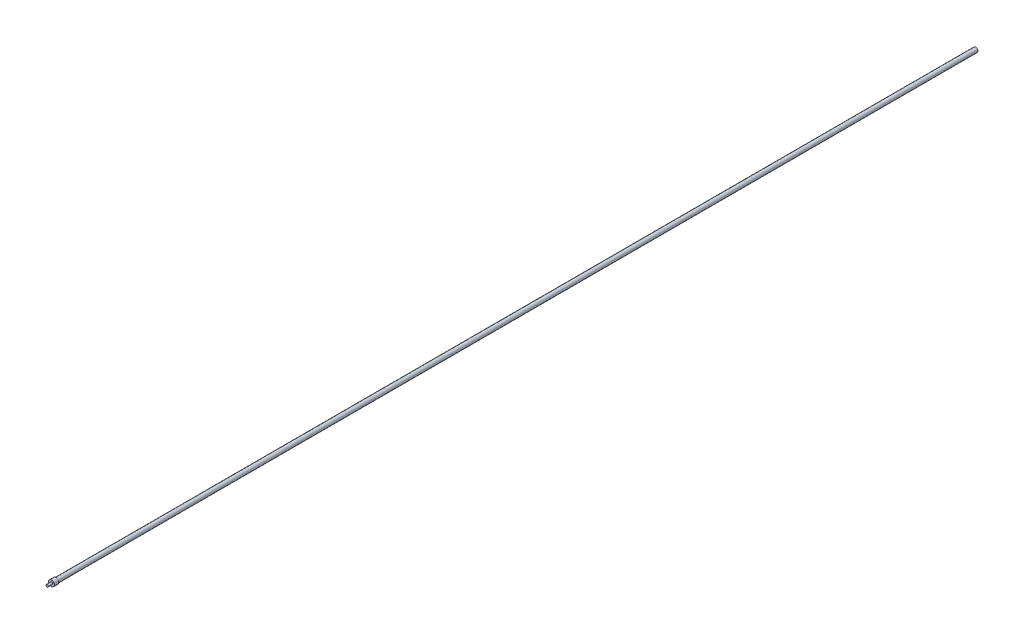
SolidWorks part; units mm, degrees
ref_plane "Alzado" through (0, 0, 0) normal (0, 0, 1) x (1, 0, 0)
ref_plane "Planta" through (0, 0, 0) normal (0, 1, 0) x (1, 0, 0)
ref_plane "Vista lateral" through (0, 0, 0) normal (1, 0, 0) x (0, 0, -1)
sketch "Croquis1" plane through (0, 0, 0) normal (0, 0, 1) x (1, 0, 0)
  circle A0 centre (0, 0) radius 6.35
  dimension "D1" = 12.7
extrude "Saliente-Extruir1" add sketch "Croquis1" along normal blind 2545
sketch "Croquis4" plane through (0, 0, 2545) normal (0, 0, 1) x (1, 0, 0)
  circle A0 centre (0, 0) radius 8
  dimension "D1" = 16
extrude "Saliente-Extruir2" add sketch "Croquis4" along normal blind 12
sketch "Croquis5" plane through (0, 0, 2557) normal (0, 0, 1) x (1, 0, 0)
  circle A0 centre (0, 0) radius 3.175
  dimension "D1" = 6.35
extrude "Saliente-Extruir3" add sketch "Croquis5" along normal blind 12
